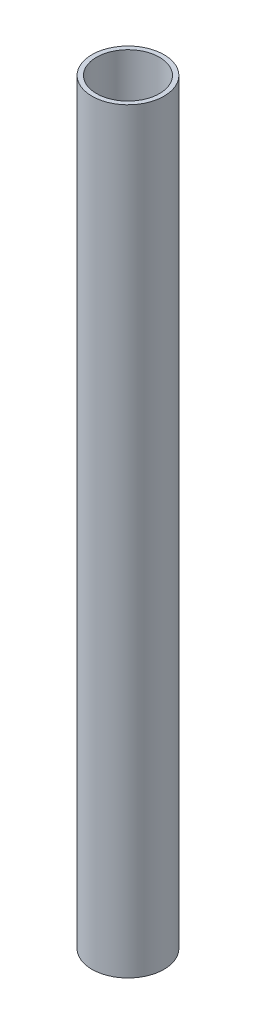
SolidWorks part; units mm, degrees
ref_plane "Front Plane" through (0, 0, 0) normal (0, 0, 1) x (1, 0, 0)
ref_plane "Top Plane" through (0, 0, 0) normal (0, 1, 0) x (1, 0, 0)
ref_plane "Right Plane" through (0, 0, 0) normal (1, 0, 0) x (0, 0, -1)
sketch "Sketch1" plane through (0, 0, 0) normal (0, 1, 0) x (1, 0, 0)
  circle A0 centre (0, 0) radius 50.8
  circle A1 centre (0, 0) radius 44.45
  dimension "D1" = 101.6
  dimension "D2" = 88.9
extrude "Boss-Extrude1" add sketch "Sketch1" along normal blind 1066.8
